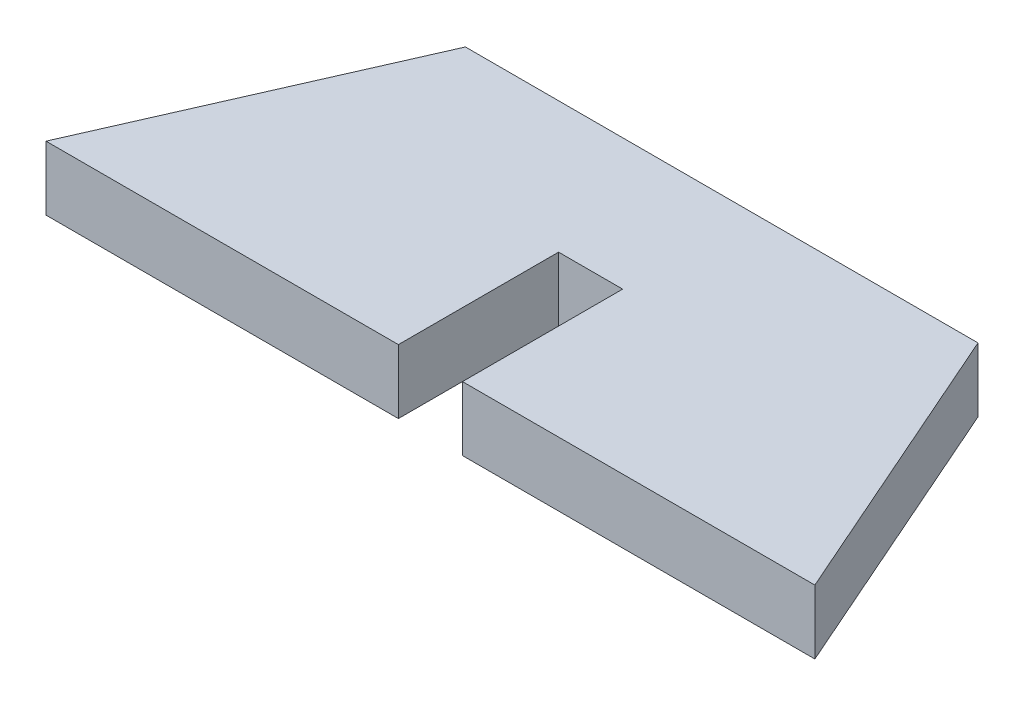
SolidWorks part; units mm, degrees
ref_plane "Спереди" through (0, 0, 0) normal (0, 0, 1) x (1, 0, 0)
ref_plane "Сверху" through (0, 0, 0) normal (0, 1, 0) x (1, 0, 0)
ref_plane "Справа" through (0, 0, 0) normal (1, 0, 0) x (0, 0, -1)
sketch "Эскиз1" plane through (0, 0, 0) normal (0, 1, 0) x (1, 0, 0)
  line L0 (-60, 0) -> (-5, 0)
  line L1 (-40, 45.4615) -> (40, 45.4615)
  line L2 (-40, 45.4615) -> (-60, 0)
  line L3 (60, 0) -> (40, 45.4615)
  line L4 (0, 22.7308) -> (-30, 22.7308) construction
  line L5 (30, 22.7308) -> (0, 22.7308) construction
  line L6 (5, 0) -> (60, 0)
  line L8 (5, 0) -> (5, 25)
  line L9 (5, 25) -> (-5, 25)
  line L10 (-5, 0) -> (-5, 25)
  point P3 (0, 0)
  point P6 (0, 45.4615)
  point P12 (0, 25)
  point P13 (0, 0)
  dimension "D3" = 10
  dimension "D1" = 120
  dimension "D2" = 80
  dimension "D6" = 30
  dimension "D7" = 25
extrude "Бобышка-Вытянуть1" add sketch "Эскиз1" along normal blind 10
